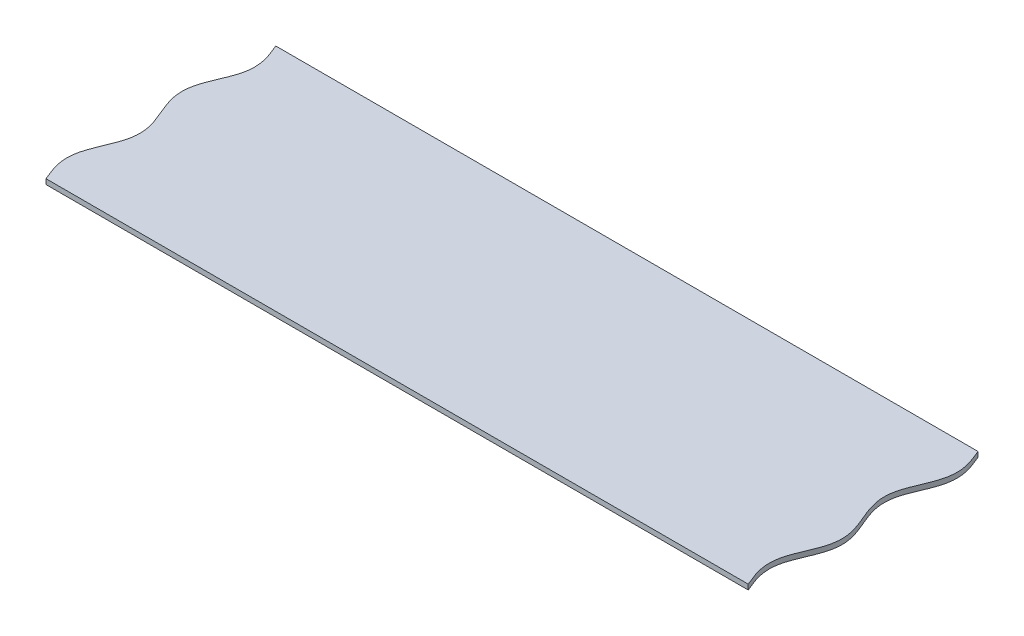
SolidWorks part; units mm, degrees
ref_plane "Front Plane" through (0, 0, 0) normal (0, 0, 1) x (1, 0, 0)
ref_plane "Top Plane" through (0, 0, 0) normal (0, 1, 0) x (1, 0, 0)
ref_plane "Right Plane" through (0, 0, 0) normal (1, 0, 0) x (0, 0, -1)
sketch "Sketch1" plane through (0, 0, 0) normal (0, 1, 0) x (1, 0, 0)
  line L0 (0, 0) -> (55, 0)
  line L2 (55, -18) -> (0, -18)
  spline S0 degree 4 poles (-0.5685, 1.7821) (-0.557, 1.6985) (-0.5295, 1.5323) (-0.4772, 1.2969) (-0.3953, 1.0229) (-0.3202, 0.8033) (-0.2254, 0.5446) (-0.03, 0.0672) (0.0329, -0.074) (0.2309, -0.5581) (0.314, -0.7865) (0.3626, -0.9275) (0.4246, -1.1203) (0.4923, -1.3616) (0.5544, -1.6497) (0.5923, -1.9494) (0.603, -2.2069) (0.5966, -2.4647) (0.5731, -2.7217) (0.5142, -3.064) (0.3993, -3.4853) (0.2509, -3.8957) (0.0855, -4.2992) (-0.0996, -4.7374) (-0.2968, -5.2207) (-0.4936, -5.797) (-0.619, -6.4834) (-0.5996, -7.2321) (-0.3812, -8.1201) (-0.0001, -9) (0.3813, -9.8798) (0.6005, -10.7677) (0.6207, -11.5162) (0.496, -12.2029) (0.2996, -12.7792) (0.1024, -13.2626) (-0.0827, -13.7009) (-0.2481, -14.1043) (-0.3967, -14.5146) (-0.5119, -14.9358) (-0.5785, -15.3205) (-0.6049, -15.6636) (-0.5963, -16.008) (-0.554, -16.3492) (-0.483, -16.6774) (-0.3929, -16.9881) (-0.2861, -17.2934) (-0.1847, -17.5561) (-0.038, -17.9103) (0.0361, -18.0854) (0.1804, -18.4332) (0.2814, -18.6932) (0.3864, -18.9903) (0.4768, -19.2947) (0.5304, -19.5328) (0.558, -19.6986) (0.5694, -19.782) knots 0 0 0 0 0 0.014933 0.029865 0.04323 0.049912 0.056594 0.083322 0.110605 0.117425 0.124246 0.131066 0.137887 0.153149 0.168412 0.183675 0.191306 0.198937 0.2142 0.229463 0.252929 0.276396 0.291658 0.306921 0.337447 0.369117 0.399642 0.430167 0.469469 0.53052 0.569821 0.600347 0.630872 0.662542 0.693068 0.70833 0.723593 0.747059 0.770526 0.785789 0.801051 0.816314 0.831577 0.846839 0.862102 0.875743 0.889384 0.903025 0.916666 0.930032 0.943398 0.956764 0.970131 0.985065 1 1 1 1 1 construction
  spline S1 degree 4 poles (0, 0) (0.0494, -0.118) (0.1111, -0.2653) (0.2309, -0.5581) (0.314, -0.7865) (0.3626, -0.9275) (0.4246, -1.1203) (0.4923, -1.3616) (0.5544, -1.6497) (0.5923, -1.9494) (0.603, -2.2069) (0.5966, -2.4647) (0.5731, -2.7217) (0.5142, -3.064) (0.3993, -3.4853) (0.2509, -3.8957) (0.0855, -4.2992) (-0.0996, -4.7374) (-0.2968, -5.2207) (-0.4936, -5.797) (-0.619, -6.4834) (-0.5996, -7.2321) (-0.3812, -8.1201) (-0.0001, -9) (0.3813, -9.8798) (0.6005, -10.7677) (0.6207, -11.5162) (0.496, -12.2029) (0.2996, -12.7792) (0.1024, -13.2626) (-0.0827, -13.7009) (-0.2481, -14.1043) (-0.3967, -14.5146) (-0.5119, -14.9358) (-0.5785, -15.3205) (-0.6049, -15.6636) (-0.5963, -16.008) (-0.554, -16.3492) (-0.483, -16.6774) (-0.3929, -16.9881) (-0.2861, -17.2934) (-0.1847, -17.5561) (-0.0741, -17.8231) (-0.0247, -17.941) (0, -18) knots 0.083322 0.083322 0.083322 0.083322 0.083322 0.110605 0.117425 0.124246 0.131066 0.137887 0.153149 0.168412 0.183675 0.191306 0.198937 0.2142 0.229463 0.252929 0.276396 0.291658 0.306921 0.337447 0.369117 0.399642 0.430167 0.469469 0.53052 0.569821 0.600347 0.630872 0.662542 0.693068 0.70833 0.723593 0.747059 0.770526 0.785789 0.801051 0.816314 0.831577 0.846839 0.862102 0.875743 0.889384 0.903025 0.916666 0.916666 0.916666 0.916666 0.916666
  spline S2 degree 4 poles (54.4315, 1.7821) (54.443, 1.6985) (54.4705, 1.5323) (54.5228, 1.2969) (54.6047, 1.0229) (54.6798, 0.8033) (54.7746, 0.5446) (54.97, 0.0672) (55.0329, -0.074) (55.2309, -0.5581) (55.314, -0.7865) (55.3626, -0.9275) (55.4246, -1.1203) (55.4923, -1.3616) (55.5544, -1.6497) (55.5923, -1.9494) (55.603, -2.2069) (55.5966, -2.4647) (55.5731, -2.7217) (55.5142, -3.064) (55.3993, -3.4853) (55.2509, -3.8957) (55.0855, -4.2992) (54.9004, -4.7374) (54.7032, -5.2207) (54.5064, -5.797) (54.381, -6.4834) (54.4004, -7.2321) (54.6188, -8.1201) (54.9999, -9) (55.3813, -9.8798) (55.6005, -10.7677) (55.6207, -11.5162) (55.496, -12.2029) (55.2996, -12.7792) (55.1024, -13.2626) (54.9173, -13.7009) (54.7519, -14.1043) (54.6033, -14.5146) (54.4881, -14.9358) (54.4215, -15.3205) (54.3951, -15.6636) (54.4037, -16.008) (54.446, -16.3492) (54.517, -16.6774) (54.6071, -16.9881) (54.7139, -17.2934) (54.8153, -17.5561) (54.962, -17.9103) (55.0361, -18.0854) (55.1804, -18.4332) (55.2814, -18.6932) (55.3864, -18.9903) (55.4768, -19.2947) (55.5304, -19.5328) (55.558, -19.6986) (55.5694, -19.782) knots 0 0 0 0 0 0.014933 0.029865 0.04323 0.049912 0.056594 0.083322 0.110605 0.117425 0.124246 0.131066 0.137887 0.153149 0.168412 0.183675 0.191306 0.198937 0.2142 0.229463 0.252929 0.276396 0.291658 0.306921 0.337447 0.369117 0.399642 0.430167 0.469469 0.53052 0.569821 0.600347 0.630872 0.662542 0.693068 0.70833 0.723593 0.747059 0.770526 0.785789 0.801051 0.816314 0.831577 0.846839 0.862102 0.875743 0.889384 0.903025 0.916666 0.930032 0.943398 0.956764 0.970131 0.985065 1 1 1 1 1 construction
  spline S3 degree 4 poles (55, 0) (55.0494, -0.118) (55.1111, -0.2653) (55.2309, -0.5581) (55.314, -0.7865) (55.3626, -0.9275) (55.4246, -1.1203) (55.4923, -1.3616) (55.5544, -1.6497) (55.5923, -1.9494) (55.603, -2.2069) (55.5966, -2.4647) (55.5731, -2.7217) (55.5142, -3.064) (55.3993, -3.4853) (55.2509, -3.8957) (55.0855, -4.2992) (54.9004, -4.7374) (54.7032, -5.2207) (54.5064, -5.797) (54.381, -6.4834) (54.4004, -7.2321) (54.6188, -8.1201) (54.9999, -9) (55.3813, -9.8798) (55.6005, -10.7677) (55.6207, -11.5162) (55.496, -12.2029) (55.2996, -12.7792) (55.1024, -13.2626) (54.9173, -13.7009) (54.7519, -14.1043) (54.6033, -14.5146) (54.4881, -14.9358) (54.4215, -15.3205) (54.3951, -15.6636) (54.4037, -16.008) (54.446, -16.3492) (54.517, -16.6774) (54.6071, -16.9881) (54.7139, -17.2934) (54.8153, -17.5561) (54.9259, -17.8231) (54.9753, -17.941) (55, -18) knots 0.083322 0.083322 0.083322 0.083322 0.083322 0.110605 0.117425 0.124246 0.131066 0.137887 0.153149 0.168412 0.183675 0.191306 0.198937 0.2142 0.229463 0.252929 0.276396 0.291658 0.306921 0.337447 0.369117 0.399642 0.430167 0.469469 0.53052 0.569821 0.600347 0.630872 0.662542 0.693068 0.70833 0.723593 0.747059 0.770526 0.785789 0.801051 0.816314 0.831577 0.846839 0.862102 0.875743 0.889384 0.903025 0.916666 0.916666 0.916666 0.916666 0.916666
  point P3 (55, -0.3308)
  point P4 (55, -18.3322)
  point P5 (55.0896, -18)
  dimension "D4" = 18
  dimension "D5" = 55
extrude "Boss-Extrude1" add sketch "Sketch1" along normal blind 0.4
